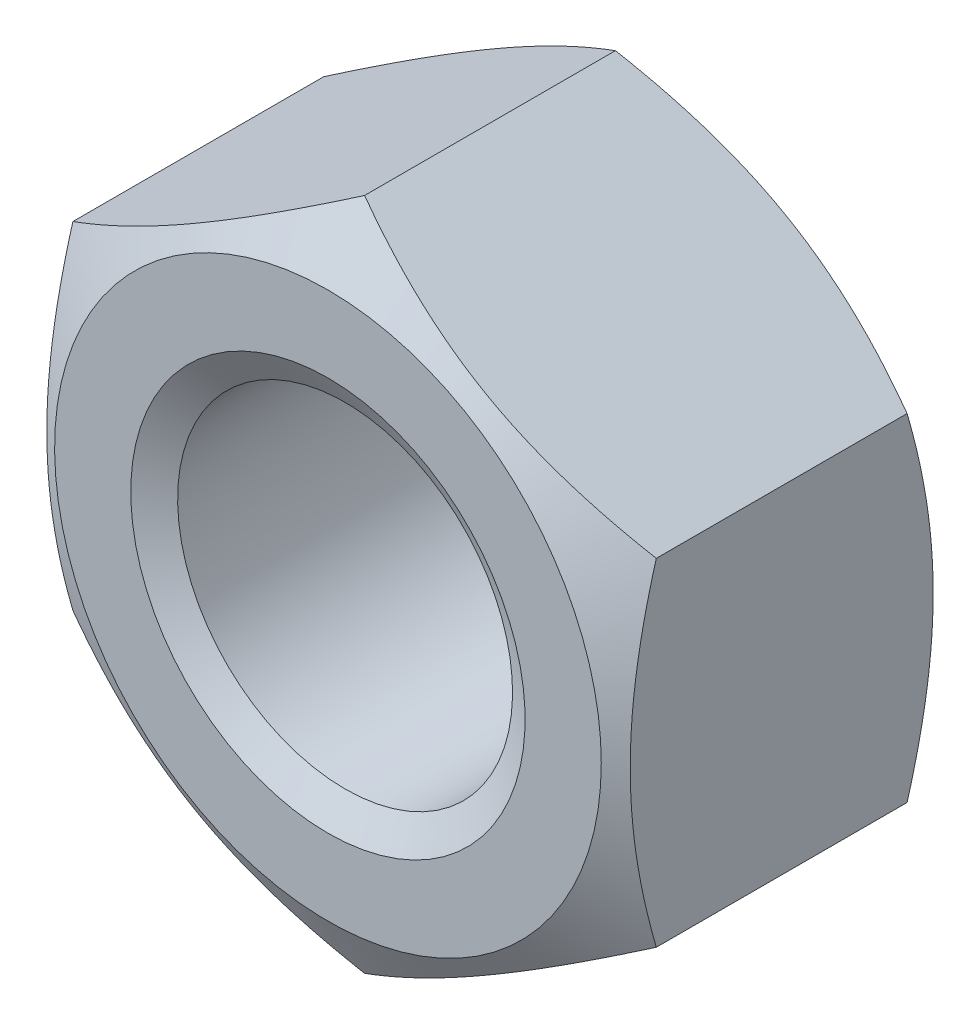
SolidWorks part; units mm, degrees
ref_plane "Front Plane" through (0, 0, 0) normal (0, 0, 1) x (1, 0, 0)
ref_plane "Top Plane" through (0, 0, 0) normal (0, 1, 0) x (1, 0, 0)
ref_plane "Right Plane" through (0, 0, 0) normal (1, 0, 0) x (0, 0, -1)
sketch "Sketch1" plane through (0, 0, 0) normal (0, 0, 1) x (1, 0, 0)
  line L0 (0, 0) -> (0, 15.5885) construction
  line L1 (0, 15.5885) -> (-13.5, 7.7942)
  line L2 (-13.5, 7.7942) -> (-13.5, -7.7942)
  line L3 (-13.5, -7.7942) -> (0, -15.5885)
  line L4 (0, -15.5885) -> (13.5, -7.7942)
  line L5 (13.5, -7.7942) -> (13.5, 7.7942)
  line L6 (13.5, 7.7942) -> (0, 15.5885)
  circle A0 centre (0, 0) radius 13.5 construction
  dimension "S DIM" = 27
extrude "Boss-Extrude1" add sketch "Sketch1" against normal blind 15
sketch "Sketch4" plane through (0, 0, 0) normal (1, 0, 0) x (0, 0, -1)
  line L0 (15, 15.5885) -> (13.3035, 15.5885)
  line L1 (15, 15.5885) -> (0, 15.5885) construction
  line L2 (13.3035, 15.5885) -> (15, 12.65)
  line L4 (15, 12.65) -> (15, 15.5885)
  line L5 (0, 0) -> (3.2979, 0) construction
  line L6 (0, 15.5885) -> (1.6965, 15.5885)
  line L7 (1.6965, 15.5885) -> (0, 12.65)
  line L9 (0, 12.65) -> (0, 15.5885)
  dimension "SAME S 1" = 25.3
  dimension "D2" = 30
  dimension "SAME S 2" = 25.3
  dimension "D4" = 30
revolve "Cut-Revolve1" cut sketch "Sketch4" angle 360 about L5
sketch "Sketch5" plane through (0, 0, 0) normal (1, 0, 0) x (0, 0, -1)
  line L0 (0, 0) -> (15, 0) construction
  line L1 (0, 0) -> (0, 9.125)
  line L2 (0, 12.65) -> (0, -12.65) construction
  line L3 (0, 9.125) -> (0.7939, 7.75)
  line L4 (0.7939, 7.75) -> (14.2061, 7.75)
  line L5 (14.2061, 7.75) -> (15, 9.125)
  line L6 (15, 9.125) -> (15, 0)
  line L8 (15, -12.65) -> (15, 12.65) construction
  line L9 (15, 0) -> (0, 0)
  dimension "D1" = 60
  dimension "D2" = 60
  dimension "Hole2" = 18.25
  dimension "Hole1" = 15.5
revolve "Cut-Revolve2" cut sketch "Sketch5" angle 360 about L0
cosmetic thread "Cosmetic Thread1" parameters "D2"=18
